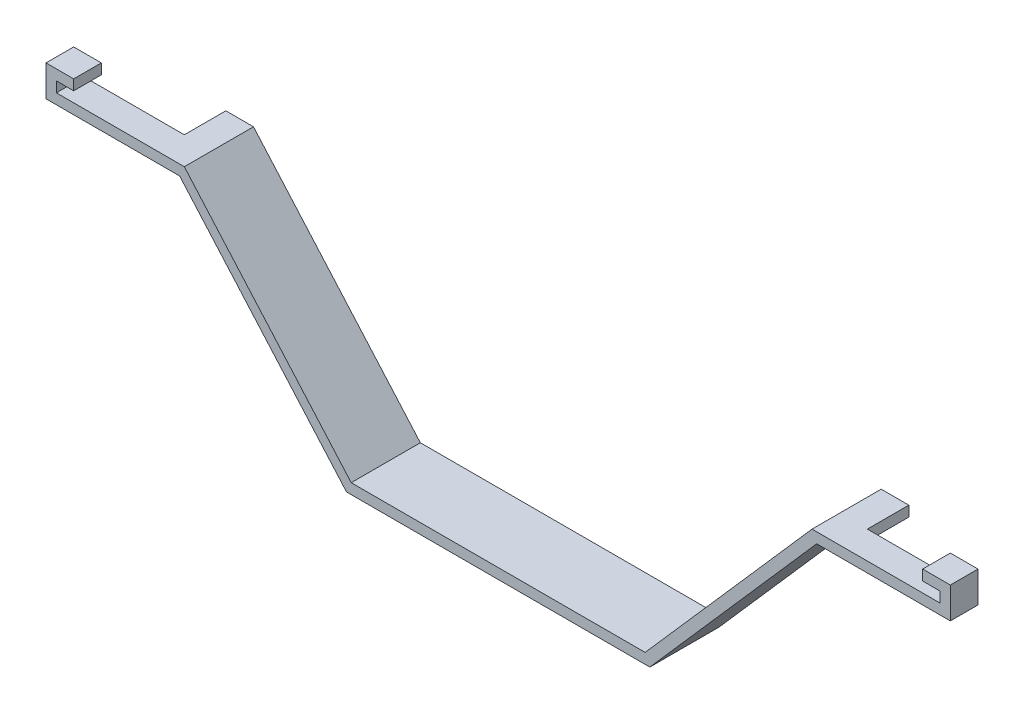
SolidWorks part; units mm, degrees
ref_plane "Front Plane" through (0, 0, 0) normal (0, 0, 1) x (1, 0, 0)
ref_plane "Top Plane" through (0, 0, 0) normal (0, 1, 0) x (1, 0, 0)
ref_plane "Right Plane" through (0, 0, 0) normal (1, 0, 0) x (0, 0, -1)
sketch "Sketch1" plane through (0, 0, 0) normal (0, 0, 1) x (1, 0, 0)
  line L0 (-173.9256, 29.589) -> (-136.9256, 29.589)
  line L5 (-46.1756, 66.1932) -> (-46.1756, -72.0417) construction
  line L6 (-176.9256, 26.589) -> (-138.2846, 26.589)
  line L7 (-90.0346, -28.411) -> (-2.2767, -28.411) construction
  line L11 (-176.9256, 26.589) -> (-138.2846, 26.589) construction
  line L15 (62.0744, 29.1932) -> (46.059, 29.1932) construction
  line L17 (-138.2846, 26.589) -> (-90.0346, -28.411) construction
  line L18 (-2.2767, -28.411) -> (46.059, 29.1932) construction
  line L22 (-176.9256, 26.589) -> (-176.9256, 35.589)
  line L24 (-173.9256, 32.589) -> (-173.9256, 29.589)
  line L25 (-176.9256, 29.589) -> (-136.9256, 29.589) construction
  line L26 (-176.9256, 35.589) -> (-168.9256, 35.589)
  line L27 (-168.9256, 35.589) -> (-168.9256, 32.589)
  line L28 (-168.9256, 32.589) -> (-173.9256, 32.589)
  line L29 (-88.6756, -25.411) -> (-3.6756, -25.411) construction
  line L33 (-3.6756, -25.411) -> (44.6601, 32.1932) construction
  line L34 (62.0744, 32.1932) -> (44.6601, 32.1932) construction
  line L38 (-136.9256, 29.589) -> (-88.6756, -25.411) construction
  line L39 (-138.2846, 26.589) -> (-90.0346, -28.411)
  line L40 (-136.9256, 29.589) -> (-88.6756, -25.411)
  line L41 (-88.6756, -25.411) -> (-3.6756, -25.411)
  line L42 (-90.0346, -28.411) -> (-2.3166, -28.411)
  line L43 (44.5744, 29.589) -> (-3.6756, -25.411)
  line L44 (45.9334, 26.589) -> (-2.3166, -28.411)
  line L45 (76.5744, 32.589) -> (81.5744, 32.589)
  line L46 (76.5744, 35.589) -> (76.5744, 32.589)
  line L47 (84.5744, 35.589) -> (76.5744, 35.589)
  line L48 (81.5744, 32.589) -> (81.5744, 29.589)
  line L49 (84.5744, 26.589) -> (84.5744, 35.589)
  line L50 (84.5744, 26.589) -> (45.9334, 26.589)
  line L51 (81.5744, 29.589) -> (44.5744, 29.589)
  point P6 (-171.4256, 32.589)
  point P17 (-46.1756, -25.411)
  point P21 (-46.1756, -28.411)
  point P23 (-46.1756, -25.411)
  point P32 (-46.1756, -28.411)
  dimension "D1" = 3
  dimension "D2" = 3
  dimension "D3" = 3
  dimension "D4" = 3
  dimension "D7" = 130.75
  dimension "D8" = 42.5
  dimension "D9" = 8
  dimension "D10" = 40
  dimension "D11" = 3
extrude "Boss-Extrude1" add sketch "Sketch1" along normal blind 20
sketch "Sketch2" plane through (0, 35.589, 0) normal (0, 1, 0) x (1, 0, 0)
  line L2 (-46.1756, 46.6347) -> (-46.1756, -72.5419) construction
  line L7 (-3.6756, 0) -> (-88.6756, 0) construction
  line L8 (-168.9256, 0) -> (-176.9256, 0) construction
  line L10 (-176.9256, -12) -> (-144.9256, -12)
  line L11 (-176.9256, -12) -> (-176.9256, 12)
  line L16 (-176.9256, 12) -> (-144.9256, 12)
  line L17 (-144.9256, -12) -> (-144.9256, 12)
  line L18 (84.5744, 12) -> (52.5744, 12)
  line L19 (52.5744, -12) -> (52.5744, 12)
  line L20 (84.5744, -12) -> (52.5744, -12)
  line L21 (84.5744, -12) -> (84.5744, 12)
  point P7 (-46.1756, 0)
  dimension "D1" = 24
  dimension "D2" = 32
  dimension "D3" = 12
extrude "Cut-Extrude1" cut sketch "Sketch2" against normal through all
